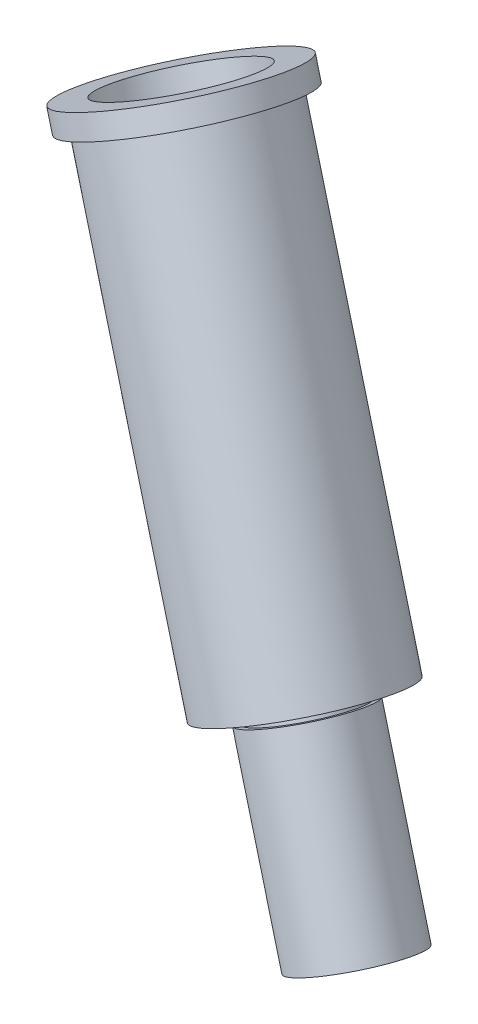
SolidWorks part; units mm, degrees
other "Markup1"
sketch "Sketch7" plane through (-206.0284, 201.4318, -3.7457) normal (-0.8382, 0.5448, -0.0267) x (0.4541, 0.7241, 0.5191)
ref_plane "Front Plane" through (0, 0, 0) normal (0, 0, 1) x (1, 0, 0)
ref_plane "Top Plane" through (0, 0, 0) normal (0, 1, 0) x (1, 0, 0)
ref_plane "Right Plane" through (0, 0, 0) normal (1, 0, 0) x (0, 0, -1)
sketch "Sketch1" plane through (-129.2035, 253.122, -50.2713) normal (-0.4477, 0.8771, -0.1742) x (0.8839, 0.4046, -0.2345)
  circle A0 centre (-31.0857, -28.5191) radius 11.43
  dimension "D1" = 22.86
extrude "Boss-Extrude1" add sketch "Sketch1" along normal blind 2.54 contours A0
sketch "Sketch2" plane through (-129.2035, 253.122, -50.2713) normal (0.4477, -0.8771, 0.1742) x (-0.8839, -0.4046, 0.2345)
  circle A0 centre (31.0857, -28.5191) radius 9.9949
  dimension "D1" = 19.9898
extrude "Boss-Extrude2" add sketch "Sketch2" along normal up to surface (50.8 mm away)
sketch "Sketch3" plane through (-106.461, 208.5673, -41.4226) normal (0.4477, -0.8771, 0.1742) x (-0.8839, -0.4046, 0.2345)
  line L0 (33.4658, -38.4046) -> (28.7055, -18.6336) construction
  circle A0 centre (31.0857, -28.5191) radius 5.715
  dimension "D1" = 11.43
extrude "Boss-Extrude3" add sketch "Sketch3" along normal blind 1.016 contours A0
sketch "Sketch4" plane through (-106.0061, 207.6762, -41.2456) normal (0.4477, -0.8771, 0.1742) x (-0.8839, -0.4046, 0.2345)
  line L0 (39.2348, -26.557) -> (22.9365, -30.4812) construction
  circle A0 centre (31.0857, -28.5191) radius 6.35
  dimension "D1" = 12.7
extrude "Boss-Extrude4" add sketch "Sketch4" along normal blind 21.336 contours A0
sketch "Sketch5" plane through (-130.3406, 255.3497, -50.7138) normal (-0.4477, 0.8771, -0.1742) x (0.8839, 0.4046, -0.2345)
  line L0 (-33.4658, -38.4046) -> (-28.7055, -18.6336) construction
  circle A0 centre (-31.0857, -28.5191) radius 3.175
  dimension "D1" = 6.35
extrude "Cut-Extrude1" cut sketch "Sketch5" against normal through all
sketch "Sketch6" plane through (-130.3406, 255.3497, -50.7138) normal (-0.4477, 0.8771, -0.1742) x (0.8839, 0.4046, -0.2345)
  circle A0 centre (-31.0857, -28.5191) radius 7.9375
  dimension "D1" = 15.875
extrude "Cut-Extrude2" cut sketch "Sketch6" against normal blind 38.1
